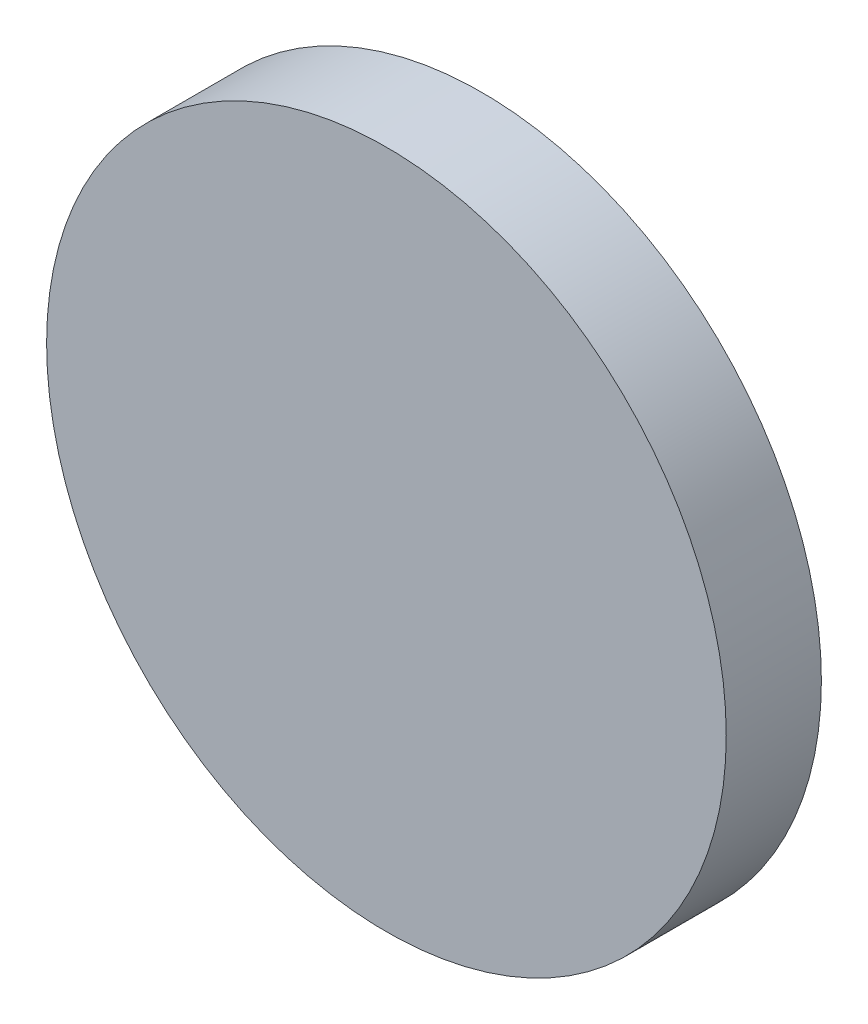
SolidWorks part; units mm, degrees
ref_plane "Front Plane" through (0, 0, 0) normal (0, 0, 1) x (1, 0, 0)
ref_plane "Top Plane" through (0, 0, 0) normal (0, 1, 0) x (1, 0, 0)
ref_plane "Right Plane" through (0, 0, 0) normal (1, 0, 0) x (0, 0, -1)
sketch "Sketch1" plane through (0, 0, 0) normal (0, 0, 1) x (1, 0, 0)
  circle A0 centre (0, 0) radius 25
  dimension "D1" = 50
extrude "Boss-Extrude1" add sketch "Sketch1" along normal blind 7
sketch "Sketch2" plane through (0, 0, 0) normal (0, 0, -1) x (-1, 0, 0)
  circle A0 centre (0, 0) radius 3.5
  dimension "D1" = 7
extrude "Cut-Extrude1" cut sketch "Sketch2" against normal blind 5
